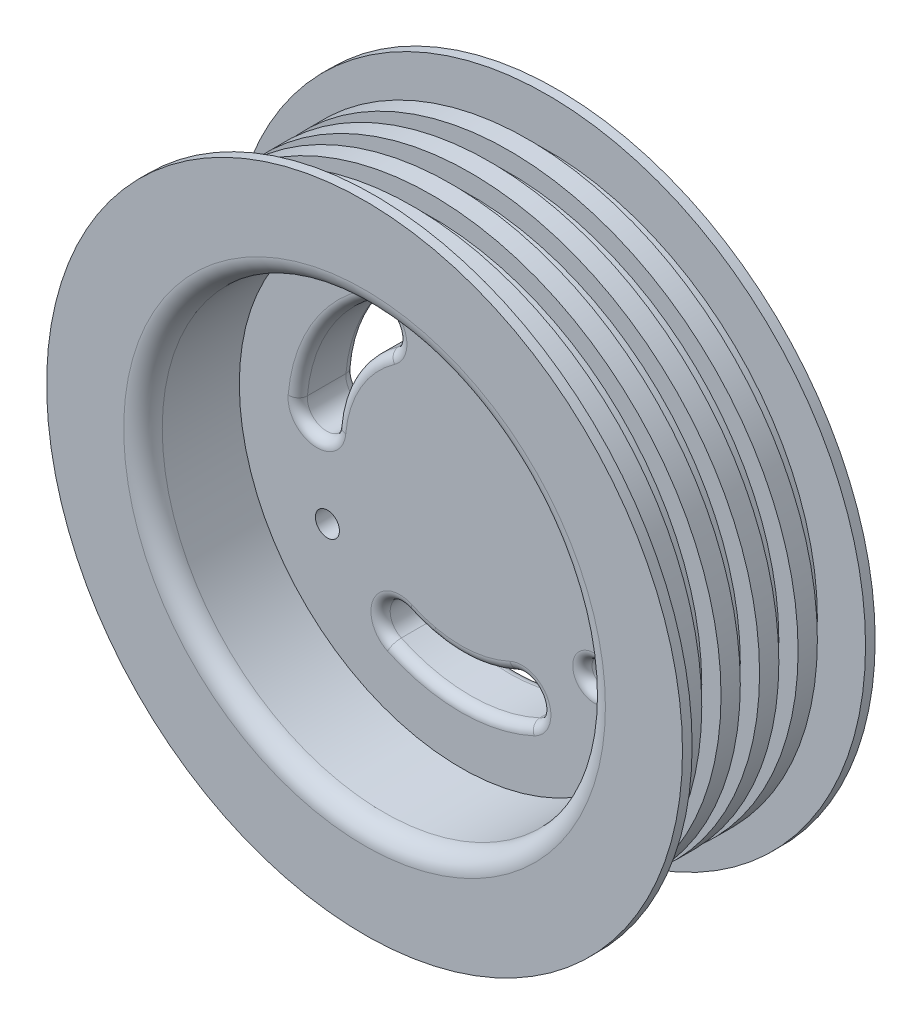
SolidWorks part; units mm, degrees
ref_plane "Front Plane" through (0, 0, 0) normal (0, 0, 1) x (1, 0, 0)
ref_plane "Top Plane" through (0, 0, 0) normal (0, 1, 0) x (1, 0, 0)
ref_plane "Right Plane" through (0, 0, 0) normal (1, 0, 0) x (0, 0, -1)
sketch "Sketch1" plane through (0, 0, 0) normal (0, 0, 1) x (1, 0, 0)
  circle A0 centre (0, 0) radius 33
  dimension "D1" = 66
extrude "Boss-Extrude1" add sketch "Sketch1" along normal blind 20
shell "Shell1" thickness 10
sketch "Sketch2" plane through (0, 0, 0) normal (0, 1, 0) x (1, 0, 0)
  line L0 (33, -20) -> (33, 0) construction
  line L1 (33, -1) -> (30, -1)
  line L2 (33, -1) -> (33, -19)
  line L3 (33, -19) -> (30, -19)
  line L4 (30, -1) -> (30, -19)
  line L5 (33, 0) -> (-33, 0) construction
  line L6 (-33, -20) -> (33, -20) construction
  dimension "D1" = 1
  dimension "D2" = 1
  dimension "D3" = 3
revolve "Cut-Revolve1" cut sketch "Sketch2" angle 360 about axis through (0, 0, 20) along (0, 0, -1)
sketch "Sketch3" plane through (0, 0, 0) normal (0, 1, 0) x (1, 0, 0)
  line L1 (30, -1) -> (28, -1)
  line L2 (30, -1) -> (30, -3)
  line L3 (30, -3) -> (28, -3)
  line L4 (28, -1) -> (28, -3)
  dimension "D1" = 2
  dimension "D2" = 2
revolve "Cut-Revolve2" cut sketch "Sketch3" angle 360 about axis through (0, 0, 20) along (0, 0, -1)
pattern_linear "LPattern1" count 5 spacing 4 along (0, 0, 1) of "Cut-Revolve2"
sketch "Sketch5" plane through (0, 0, 0) normal (0, 0, 1) x (1, 0, 0)
  line L0 (-16.4545, -6.5) -> (-2.5981, 17.5)
  line L1 (2.5981, 17.5) -> (16.4545, -6.5)
  line L2 (13.8564, -11) -> (-13.8564, -11)
  circle A0 centre (0, 0) radius 11 construction
  arc A3 (-16.4545, -6.5) -> (-13.8564, -11) centre (-13.8564, -8) ccw
  arc A4 (16.4545, -6.5) -> (13.8564, -11) centre (13.8564, -8) cw
  arc A5 (-2.5981, 17.5) -> (2.5981, 17.5) centre (0, 16) cw
  circle A6 centre (0, 0) radius 23 construction
  circle A7 centre (0, 0) radius 23
  dimension "D1" = 22
  dimension "D2" = 3
extrude "Cut-Extrude1" cut sketch "Sketch5" along normal blind 4
hole_wizard "Tap Drill for M3 Tap1" positions "Sketch7" profile "Sketch8" hole size "M3" standard "ISO" end condition through all
sketch "Sketch7" plane through (0, 0, 0) normal (0, 0, -1) x (-1, 0, 0)
  point P0 (0, 16)
  point P3 (13.8564, -8)
  point P6 (-13.8564, -8)
sketch "Sketch8" plane through (0, 16, 0) normal (1, 0, 0) x (0, 1, 0)
  line L0 (0, 0) -> (0, 20)
  line L1 (0, 20) -> (1.25, 20)
  line L2 (1.25, 20) -> (1.25, 0.025)
  line L3 (1.25, 0.025) -> (1.275, 0)
  line L5 (1.275, 0) -> (0, 0)
  line L6 (-1.25, 0.025) -> (-1.275, 0) construction
  line L11 (0, -6.35) -> (0, 107.95) construction
  dimension "Thru Hole Dia." = 2.5
  dimension "Thru Hole Depth" = 20
  dimension "Near C'Sink Dia." = 2.55
  dimension "Near C'Sink Angle" = 90
sketch "Sketch9" plane through (0, 0, 0) normal (0, 0, -1) x (-1, 0, 0)
  circle A0 centre (0, 0) radius 5
  dimension "D1" = 10
extrude "Cut-Extrude2" cut sketch "Sketch9" against normal blind 9
chamfer "Chamfer1" distance 1 angle 45 1 edges at (-5, 0, 0)
sketch "Sketch10" plane through (0, 0, 4) normal (0, 0, -1) x (-1, 0, 0)
  line L0 (8.6036, 12.2873) -> (0, 0) construction
  line L1 (0, 0) -> (0, 40.4587) construction
  line L2 (0, 0) -> (34.1809, 19.7343) construction
  line L3 (0, 0) -> (14.9429, 1.3073) construction
  arc A0 (8.6036, 12.2873) -> (14.9429, 1.3073) centre (0, 0) cw construction
  arc A1 (16.9353, 1.4816) -> (9.7508, 13.9256) centre (0, 0) ccw
  arc A2 (12.9505, 1.133) -> (7.4565, 10.649) centre (0, 0) ccw
  arc A3 (12.9505, 1.133) -> (16.9353, 1.4816) centre (14.9429, 1.3073) ccw
  arc A4 (9.7508, 13.9256) -> (7.4565, 10.649) centre (8.6036, 12.2873) ccw
  point P4 (12.9904, 7.5)
  dimension "D2" = 2
  dimension "D3" = 15
  dimension "D1" = 60
  dimension "D4" = 50
extrude "Cut-Extrude3" cut sketch "Sketch10" against normal through all
pattern_circular "CirPattern1" count 3 over 360 about axis through (0, 0, 0) along (0, 0, 1) of "Cut-Extrude3"
fillet "Fillet1" radius 1 14 edges at (-15.1172, -0.6851, 10) (-14.7224, 8.5, 10) (-6.9653, 13.4344, 10) (-8.1519, -12.7494, 10) (0, -13, 10) (8.1519, -12.7494, 10) (15.1172, -0.6851, 10) (11.2583, 6.5, 10) (6.9653, 13.4344, 10) (-11.2583, 6.5, 10) (0, -17, 10) (15.1064, -8, 10) (1.25, 16, 10) (14.7224, 8.5, 10)
fillet "Fillet2" radius 1 12 edges at (8.1519, -12.7494, 4) (0, -13, 4) (-8.1519, -12.7494, 4) (6.9653, 13.4344, 4) (11.2583, 6.5, 4) (15.1172, -0.6851, 4) (-6.9653, 13.4344, 4) (-14.7224, 8.5, 4) (-15.1172, -0.6851, 4) (0, -17, 4) (14.7224, 8.5, 4) (-11.2583, 6.5, 4)
fillet "Fillet3" radius 2 1 edges at (23, 0, 20)
